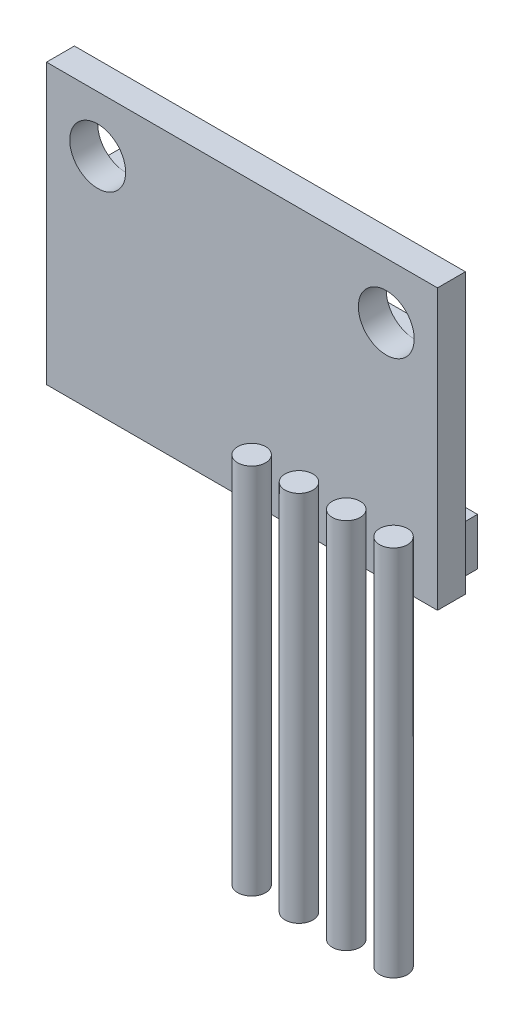
SolidWorks part; units mm, degrees
material "Hot Galvanized Steel"
ref_plane "Front" through (0, 0, 0) normal (0, 0, 1) x (1, 0, 0)
ref_plane "Top" through (0, 0, 0) normal (0, 1, 0) x (1, 0, 0)
ref_plane "Right" through (0, 0, 0) normal (1, 0, 0) x (0, 0, -1)
sketch "Sketch2" plane through (0, 0, 0) normal (0, 0, 1) x (1, 0, 0)
  line L1 (-10.5, 7.5) -> (10.5, 7.5)
  line L2 (-10.5, 7.5) -> (-10.5, -7.5)
  line L3 (-10.5, -7.5) -> (10.5, -7.5)
  line L4 (10.5, 7.5) -> (10.5, -7.5)
  line L5 (-10.5, 7.5) -> (10.5, -7.5) construction
  line L6 (-10.5, -7.5) -> (10.5, 7.5) construction
  point P0 (0, 0)
  dimension "D1" = 21
  dimension "D2" = 15
extrude "Boss-Extrude1" add sketch "Sketch2" along normal blind 1.5
sketch "Sketch3" plane through (0, 0, 1.5) normal (0, 0, 1) x (1, 0, 0)
  line L0 (0, 7.5) -> (0, 0) construction
  line L1 (10.5, 7.5) -> (-10.5, 7.5) construction
  circle A0 centre (-7.75, 4.5) radius 1.5
  circle A1 centre (7.75, 4.5) radius 1.5
  dimension "D1" = 15.5
  dimension "D2" = 3
  dimension "D3" = 3
extrude "Cut-Extrude1" cut sketch "Sketch3" against normal through all
sketch "Sketch4" plane through (0, 0, 1.5) normal (0, 0, 1) x (1, 0, 0)
  line L0 (-10.5, -7.5) -> (10.5, -7.5) construction
  line L1 (-10.15, -4.5) -> (10.15, -4.5)
  line L2 (-10.15, -4.5) -> (-10.15, -7)
  line L3 (-10.15, -7) -> (10.15, -7)
  line L4 (10.15, -4.5) -> (10.15, -7)
  line L5 (-10.15, -4.5) -> (10.15, -7) construction
  line L6 (-10.15, -7) -> (10.15, -4.5) construction
  point P0 (0, -5.75)
  dimension "D1" = 2.5
  dimension "D2" = 20.3
  dimension "D3" = 0.5
extrude "Boss-Extrude2" [suppressed] add sketch "Sketch4" along normal blind 2.5
sketch "Sketch5" [suppressed] plane through (0, 0, 4) normal (0, 0, 1) x (1, 0, 0)
  line L0 (-10.15, -4.5) -> (-10.15, -7) construction
  line L1 (-9.14, -5.5) -> (-8.64, -5.5)
  line L2 (-9.14, -5.5) -> (-9.14, -6)
  line L3 (-9.14, -6) -> (-8.64, -6)
  line L4 (-8.64, -5.5) -> (-8.64, -6)
  line L5 (-9.14, -5.5) -> (-8.64, -6) construction
  line L6 (-9.14, -6) -> (-8.64, -5.5) construction
  line L7 (-6.6, -5.5) -> (-6.1, -5.5)
  line L8 (-6.6, -5.5) -> (-6.6, -6)
  line L9 (-6.6, -6) -> (-6.1, -6)
  line L10 (-6.1, -5.5) -> (-6.1, -6)
  line L11 (-6.6, -5.5) -> (-6.1, -6) construction
  line L12 (-6.6, -6) -> (-6.1, -5.5) construction
  line L13 (-4.06, -5.5) -> (-3.56, -5.5)
  line L14 (-4.06, -5.5) -> (-4.06, -6)
  line L15 (-4.06, -6) -> (-3.56, -6)
  line L16 (-3.56, -5.5) -> (-3.56, -6)
  line L17 (-4.06, -5.5) -> (-3.56, -6) construction
  line L18 (-4.06, -6) -> (-3.56, -5.5) construction
  line L19 (-1.52, -5.5) -> (-1.02, -5.5)
  line L20 (-1.52, -5.5) -> (-1.52, -6)
  line L21 (-1.52, -6) -> (-1.02, -6)
  line L22 (-1.02, -5.5) -> (-1.02, -6)
  line L23 (-1.52, -5.5) -> (-1.02, -6) construction
  line L24 (-1.52, -6) -> (-1.02, -5.5) construction
  line L25 (1.02, -5.5) -> (1.52, -5.5)
  line L26 (1.02, -5.5) -> (1.02, -6)
  line L27 (1.02, -6) -> (1.52, -6)
  line L28 (1.52, -5.5) -> (1.52, -6)
  line L29 (1.02, -5.5) -> (1.52, -6) construction
  line L30 (1.02, -6) -> (1.52, -5.5) construction
  line L31 (-8.89, -5.75) -> (-6.35, -5.75) construction
  line L32 (3.56, -5.5) -> (4.06, -5.5)
  line L33 (3.56, -5.5) -> (3.56, -6)
  line L34 (3.56, -6) -> (4.06, -6)
  line L35 (4.06, -5.5) -> (4.06, -6)
  line L36 (3.56, -5.5) -> (4.06, -6) construction
  line L37 (3.56, -6) -> (4.06, -5.5) construction
  line L38 (6.1, -5.5) -> (6.6, -5.5)
  line L39 (6.1, -5.5) -> (6.1, -6)
  line L40 (6.1, -6) -> (6.6, -6)
  line L41 (6.6, -5.5) -> (6.6, -6)
  line L42 (6.1, -5.5) -> (6.6, -6) construction
  line L43 (6.1, -6) -> (6.6, -5.5) construction
  line L44 (8.64, -5.5) -> (9.14, -5.5)
  line L45 (8.64, -5.5) -> (8.64, -6)
  line L46 (8.64, -6) -> (9.14, -6)
  line L47 (9.14, -5.5) -> (9.14, -6)
  line L48 (8.64, -5.5) -> (9.14, -6) construction
  line L49 (8.64, -6) -> (9.14, -5.5) construction
  line L50 (-1.27, -5.75) -> (1.27, -5.75) construction
  point P0 (-8.89, -5.75)
  point P7 (-10.15, -5.75)
  point P8 (3.81, -5.75)
  point P9 (-6.35, -5.75)
  point P14 (-3.81, -5.75)
  point P19 (-1.27, -5.75)
  point P24 (1.27, -5.75)
  point P36 (6.35, -5.75)
  point P41 (8.89, -5.75)
  point P46 (0, -5.75)
  dimension "D1" = 0.5
  dimension "D2" = 8
  dimension "D3" = 2.54
extrude "Boss-Extrude3" [suppressed] add sketch "Sketch5" along normal blind 5.5
chamfer "Chamfer1" [suppressed] distance 0.3 angle 20
sketch "Sketch7" plane through (0, -7.5, 0) normal (0, -1, 0) x (1, 0, 0)
  line L0 (8.89, 2.25) -> (6.35, 2.25) construction
  line L1 (-10.5, 1.5) -> (10.5, 1.5) construction
  line L2 (10.5, 1.5) -> (10.5, 0) construction
  circle A0 centre (8.89, 2.25) radius 0.75
  circle A2 centre (6.35, 2.25) radius 0.75
  circle A3 centre (3.81, 2.25) radius 0.75
  circle A4 centre (1.27, 2.25) radius 0.75
  dimension "D1" = 4
  dimension "D3" = 1.5
  dimension "D4" = 1.61
  dimension "D2" = 2.54
extrude "Boss-Extrude4" add sketch "Sketch7" along normal blind 20 from offset 3 separate body offset against normal yes
sketch "Sketch6" plane through (0, 0, 0) normal (0, 0, -1) x (-1, 0, 0)
  line L0 (10.5, -7.5) -> (-10.5, -7.5) construction
  line L1 (-10.15, -4.46) -> (10.15, -4.46)
  line L2 (-10.15, -4.46) -> (-10.15, -7)
  line L3 (-10.15, -7) -> (10.15, -7)
  line L4 (10.15, -4.46) -> (10.15, -7)
  line L5 (-10.15, -4.46) -> (10.15, -7) construction
  line L6 (-10.15, -7) -> (10.15, -4.46) construction
  line L12 (-9, 3) -> (-4, 3)
  line L17 (-9, 3) -> (-9, -1)
  line L18 (-9, -1) -> (9, -1)
  line L23 (9, 3) -> (9, -1)
  line L24 (-4, 6) -> (4, 6)
  line L26 (-4, 6) -> (-4, 3)
  line L28 (4, 6) -> (4, 3)
  line L29 (4, 3) -> (9, 3)
  line L30 (-10.5, -7.5) -> (-10.5, 7.5) construction
  circle A0 centre (-7.75, 4.5) radius 1.5 construction
  circle A1 centre (7.75, 4.5) radius 1.5 construction
  point P0 (0, -5.73)
  point P15 (0, 6)
  point P18 (9, 2.1662)
  dimension "D1" = 20.3
  dimension "D2" = 2.54
  dimension "D3" = 0.5
  dimension "D4" = 8
  dimension "D5" = 1.5
  dimension "D6" = 4
extrude "Koponenttien tilavaraus" add sketch "Sketch6" along normal blind 1
